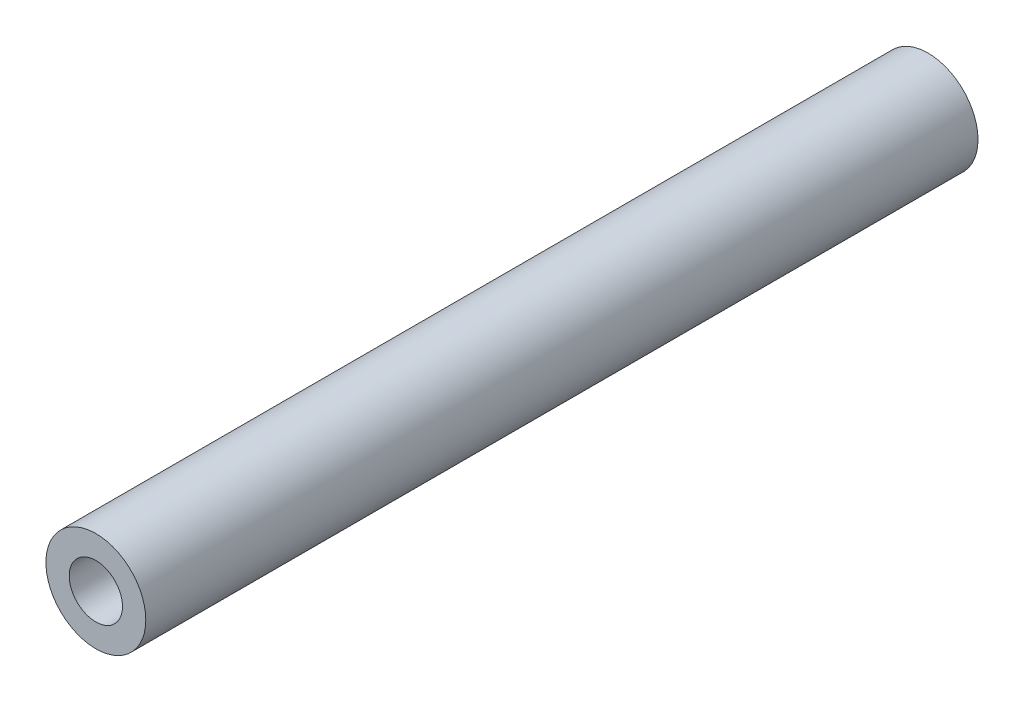
SolidWorks part; units mm, degrees
ref_plane "前视基准面" through (0, 0, 0) normal (0, 0, 1) x (1, 0, 0)
ref_plane "上视基准面" through (0, 0, 0) normal (0, 1, 0) x (1, 0, 0)
ref_plane "右视基准面" through (0, 0, 0) normal (1, 0, 0) x (0, 0, -1)
other "Configuration Table"
sketch "草图1" plane through (0, 0, 0) normal (0, 0, 1) x (1, 0, 0)
  circle A0 centre (0, 0) radius 3
  circle A1 centre (0, 0) radius 1.6
extrude "40mm铝柱" add sketch "草图1" along normal blind 50
